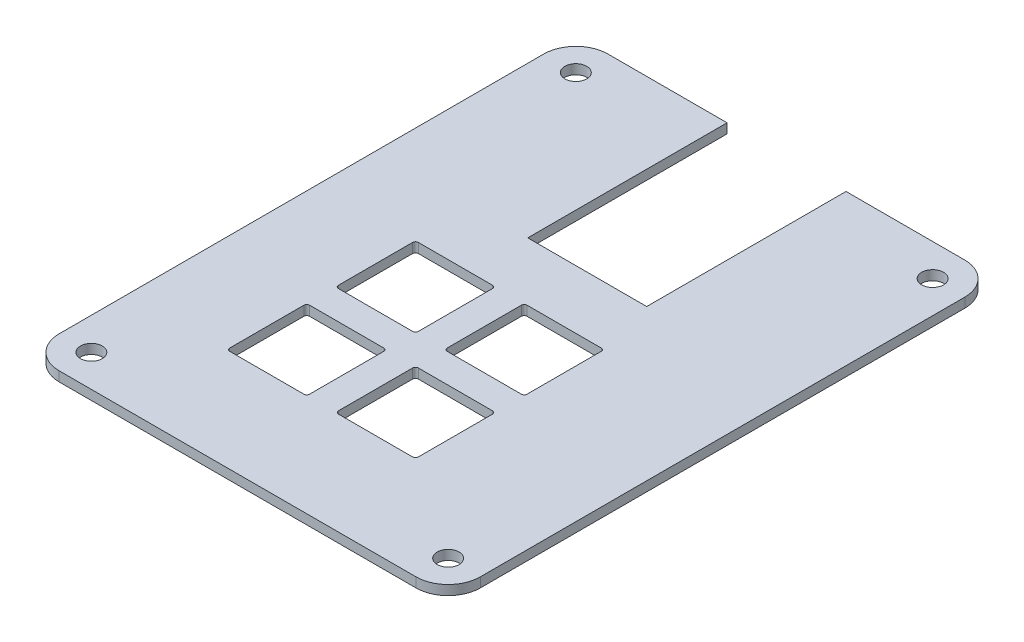
SolidWorks part; units mm, degrees
ref_plane "Front Plane" through (0, 0, 0) normal (0, 0, 1) x (1, 0, 0)
ref_plane "Top Plane" through (0, 0, 0) normal (0, 1, 0) x (1, 0, 0)
ref_plane "Right Plane" through (0, 0, 0) normal (1, 0, 0) x (0, 0, -1)
sketch "Sketch1" plane through (0, 0, 0) normal (0, 1, 0) x (1, 0, 0)
  line L0 (2.6854, -2.2415) -> (14.226, -2.2415)
  line L1 (2.6854, -14.6698) -> (14.226, -14.6698)
  line L2 (2.2415, -2.6854) -> (2.2415, -14.226)
  line L3 (14.6698, -2.6854) -> (14.6698, -14.226)
  line L4 (19.5968, -2.2415) -> (31.1373, -2.2415)
  line L5 (19.5968, -14.6698) -> (31.1373, -14.6698)
  line L6 (19.1529, -2.6854) -> (19.1529, -14.226)
  line L7 (31.5812, -2.6854) -> (31.5812, -14.226)
  line L8 (2.6854, -19.1529) -> (14.226, -19.1529)
  line L9 (2.6854, -31.5812) -> (14.226, -31.5812)
  line L10 (2.2415, -19.5968) -> (2.2415, -31.1373)
  line L11 (14.6698, -19.5968) -> (14.6698, -31.1373)
  line L12 (19.5968, -19.1529) -> (31.1373, -19.1529)
  line L13 (19.5968, -31.5812) -> (31.1373, -31.5812)
  line L14 (19.1529, -19.5968) -> (19.1529, -31.1373)
  line L15 (31.5812, -19.5968) -> (31.5812, -31.1373)
  line L16 (19.8055, 37.8828) -> (19.8055, -47.4672) construction
  line L17 (-12.9395, -47.4672) -> (52.5505, -47.4672)
  line L18 (-12.9395, -47.4672) -> (-12.9395, 37.8828)
  line L19 (-12.9395, 37.8828) -> (52.5505, 37.8828)
  line L20 (52.5505, -47.4672) -> (52.5505, 37.8828)
  line L21 (-12.9395, -4.7922) -> (52.5505, -4.7922) construction
  line L23 (10.5805, 37.8828) -> (29.0805, 37.8828)
  line L24 (10.5805, 37.8828) -> (10.5805, 6.8828)
  line L25 (10.5805, 6.8828) -> (29.0805, 6.8828)
  line L26 (29.0805, 37.8828) -> (29.0805, 6.8828)
  arc A0 (2.6854, -2.2415) -> (2.2415, -2.6854) centre (2.6854, -2.6854) ccw
  arc A1 (14.6698, -2.6854) -> (14.226, -2.2415) centre (14.226, -2.6854) ccw
  arc A2 (2.2415, -14.226) -> (2.6854, -14.6698) centre (2.6854, -14.226) ccw
  arc A3 (14.226, -14.6698) -> (14.6698, -14.226) centre (14.226, -14.226) ccw
  arc A4 (19.5968, -2.2415) -> (19.1529, -2.6854) centre (19.5968, -2.6854) ccw
  arc A5 (31.5812, -2.6854) -> (31.1373, -2.2415) centre (31.1373, -2.6854) ccw
  arc A6 (19.1529, -14.226) -> (19.5968, -14.6698) centre (19.5968, -14.226) ccw
  arc A7 (31.1373, -14.6698) -> (31.5812, -14.226) centre (31.1373, -14.226) ccw
  arc A8 (2.6854, -19.1529) -> (2.2415, -19.5968) centre (2.6854, -19.5968) ccw
  arc A9 (14.6698, -19.5968) -> (14.226, -19.1529) centre (14.226, -19.5968) ccw
  arc A10 (2.2415, -31.1373) -> (2.6854, -31.5812) centre (2.6854, -31.1373) ccw
  arc A11 (14.226, -31.5812) -> (14.6698, -31.1373) centre (14.226, -31.1373) ccw
  arc A12 (19.5968, -19.1529) -> (19.1529, -19.5968) centre (19.5968, -19.5968) ccw
  arc A13 (31.5812, -19.5968) -> (31.1373, -19.1529) centre (31.1373, -19.5968) ccw
  arc A14 (19.1529, -31.1373) -> (19.5968, -31.5812) centre (19.5968, -31.1373) ccw
  arc A15 (31.1373, -31.5812) -> (31.5812, -31.1373) centre (31.1373, -31.1373) ccw
  circle A16 centre (-7.9395, -42.4672) radius 1.7
  circle A17 centre (47.5505, -42.4672) radius 1.7
  circle A18 centre (47.5505, 32.8828) radius 1.7
  circle A19 centre (-7.9395, 32.8828) radius 1.7
  point P52 (14.6698, -25.3671)
  dimension "D5" = 3.4
  dimension "D6" = 5
  dimension "D7" = 5
  dimension "D1" = 65.49
  dimension "D2" = 85.35
  dimension "D3" = 15.886
  dimension "D4" = 15.181
  dimension "D8" = 31
  dimension "D9" = 18.5
  dimension "D10" = 23.52
extrude "Boss-Extrude1" add sketch "Sketch1" along normal blind 1.5 contours L19 L26 L25 L24 L18 L17 L20 A17 A16 A15 L13 A14 L14 A12 L12 A13 L15 A11 L9 A10 L10 A8 L8 A9 L11 A7 L5 A6 L6 A4 L4 A5 L7 A3 L1 A2 L2 A0 L0 A1 L3 A18
fillet "Fillet1" radius 5 4 edges at (-12.9395, 0.75, -37.8828) (52.5505, 0.75, -37.8828) (52.5505, 0.75, 47.4672) (-12.9395, 0.75, 47.4672)
